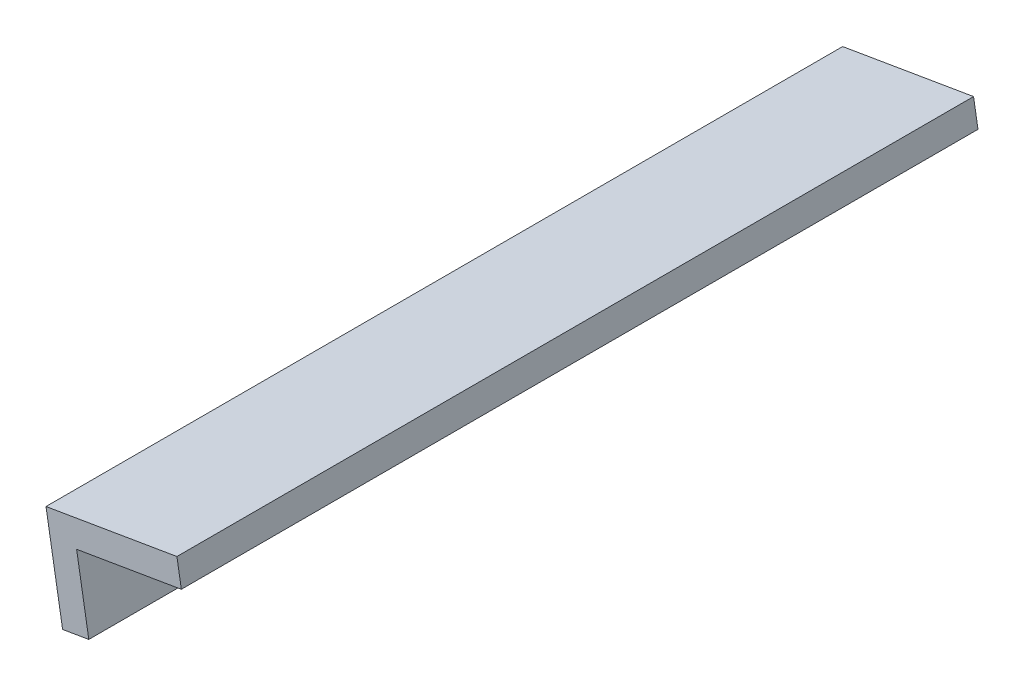
SolidWorks part; units mm, degrees
ref_plane "Front Plane" through (0, 0, 0) normal (0, 0, 1) x (1, 0, 0)
ref_plane "Top Plane" through (0, 0, 0) normal (0, 1, 0) x (1, 0, 0)
ref_plane "Right Plane" through (0, 0, 0) normal (1, 0, 0) x (0, 0, -1)
sketch "Sketch1" plane through (0, 0, 0) normal (0, 0, 1) x (1, 0, 0)
  line L0 (-124.7668, 248.5003) -> (-99.7226, 252.7369)
  line L1 (-99.7226, 252.7369) -> (-98.8753, 247.728)
  line L2 (-124.7668, 248.5003) -> (-121.5894, 229.7172)
  line L3 (-98.8753, 247.728) -> (-118.9107, 244.3388)
  line L4 (-118.9107, 244.3388) -> (-116.5806, 230.5645)
  line L5 (-116.5806, 230.5645) -> (-121.5894, 229.7172)
  dimension "D1" = 5.08
  dimension "D2" = 5.08
  dimension "D3" = 19.05
extrude "Boss-Extrude1" add sketch "Sketch1" against normal blind 152.4
